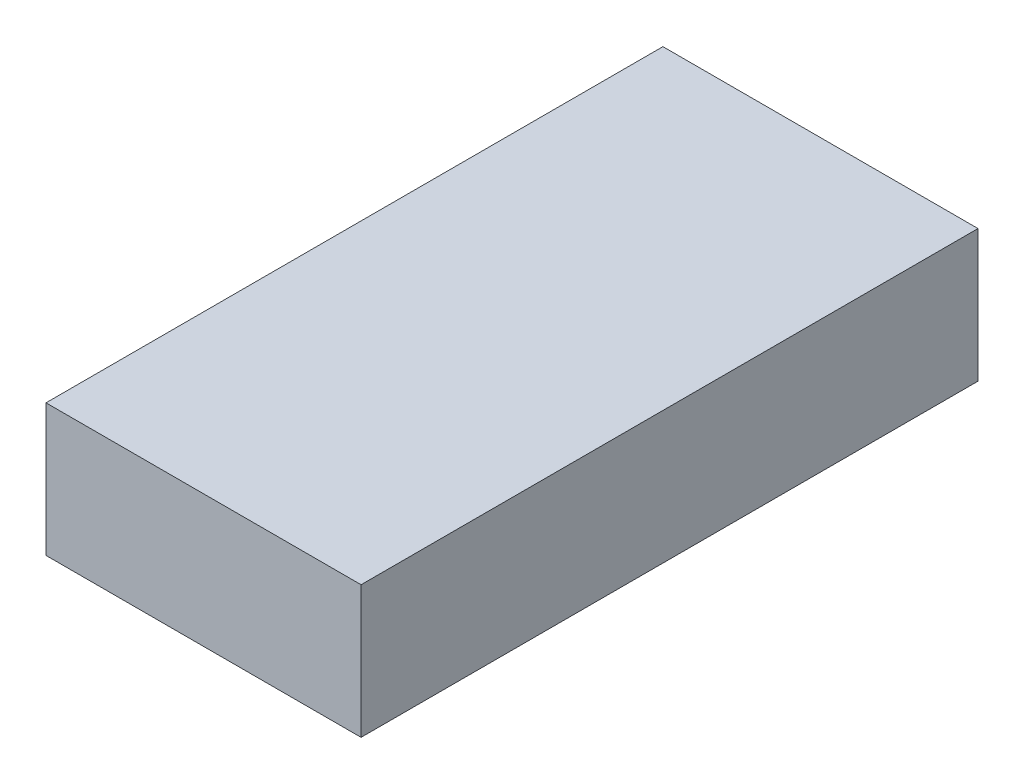
SolidWorks part; units mm, degrees
material "PLA+"
ref_plane "Front Plane" through (0, 0, 0) normal (0, 0, 1) x (1, 0, 0)
ref_plane "Top Plane" through (0, 0, 0) normal (0, 1, 0) x (1, 0, 0)
ref_plane "Right Plane" through (0, 0, 0) normal (1, 0, 0) x (0, 0, -1)
sketch "Sketch1" plane through (0, 0, 0) normal (0, 1, 0) x (1, 0, 0)
  line L0 (-5.65, 12.5) -> (-5.65, 14)
  line L1 (7.15, 14) -> (-7.15, 14)
  line L2 (7.15, 14) -> (7.15, -14)
  line L3 (7.15, -14) -> (-7.15, -14)
  line L4 (-7.15, 14) -> (-7.15, -14)
  line L5 (7.15, 14) -> (-7.15, -14) construction
  line L6 (7.15, -14) -> (-7.15, 14) construction
  line L7 (5.65, 12.5) -> (-5.65, 12.5)
  line L8 (5.65, 12.5) -> (5.65, -12.5)
  line L9 (5.65, -12.5) -> (-5.65, -12.5)
  line L10 (-5.65, 12.5) -> (-5.65, -12.5)
  line L11 (5.65, 12.5) -> (-5.65, -12.5) construction
  line L12 (5.65, -12.5) -> (-5.65, 12.5) construction
  line L15 (5.65, 14) -> (5.65, 12.5)
  point P0 (0, 0)
  point P6 (0, 0)
  dimension "D1" = 14.3
  dimension "D2" = 1.5
  dimension "D3" = 1.5
  dimension "D4" = 28
extrude "Boss-Extrude1" add sketch "Sketch1" along normal blind 4 contours L1 L15 L8 L9 L10 L0 L4 L3 L2
sketch "Sketch2" plane through (0, 4, 0) normal (0, 1, 0) x (1, 0, 0)
  line L1 (-7.15, 14) -> (7.15, 14)
  line L2 (-7.15, 14) -> (-7.15, -14)
  line L3 (-7.15, -14) -> (7.15, -14)
  line L4 (7.15, 14) -> (7.15, -14)
extrude "Boss-Extrude2" add sketch "Sketch2" along normal blind 2
